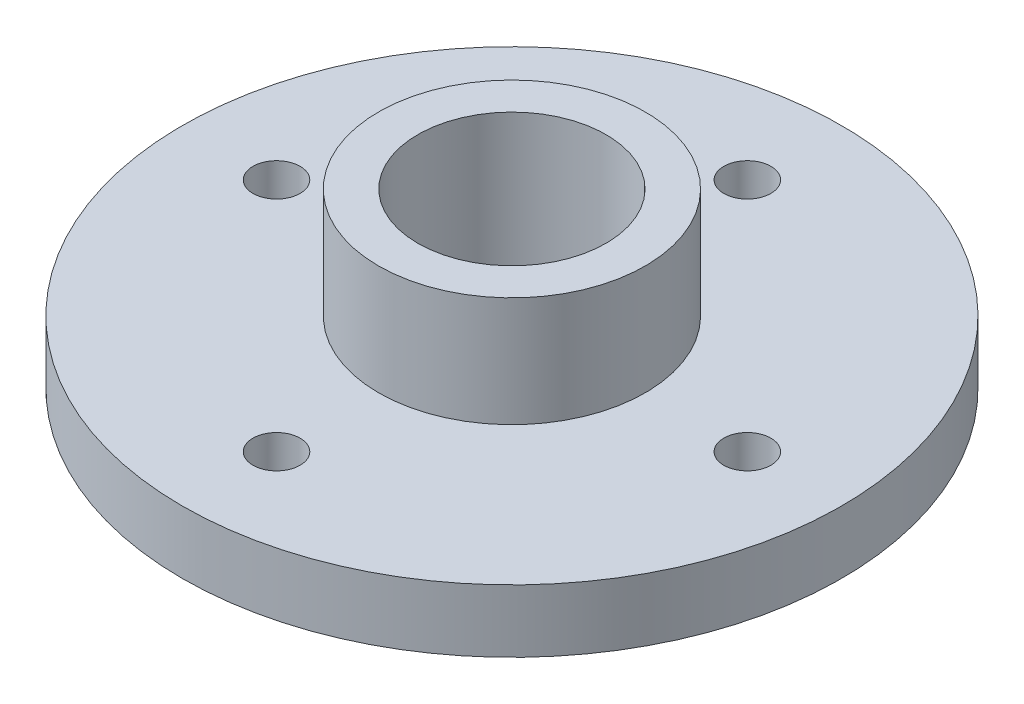
SolidWorks part; units mm, degrees
ref_plane "Vorne" through (0, 0, 0) normal (0, 0, 1) x (1, 0, 0)
ref_plane "Oben" through (0, 0, 0) normal (0, 1, 0) x (1, 0, 0)
ref_plane "Rechts" through (0, 0, 0) normal (1, 0, 0) x (0, 0, -1)
sketch "Skizze1" plane through (0, 0, 0) normal (0, 1, 0) x (1, 0, 0)
  circle A0 centre (0, 0) radius 10.5
  dimension "D1" = 21
extrude "Aufsatz-Linear austragen1" add sketch "Skizze1" along normal blind 2
sketch "Skizze2" plane through (0, 2, 0) normal (0, 1, 0) x (1, 0, 0)
  circle A0 centre (0, 0) radius 4.25
  circle A1 centre (0, 0) radius 3
  dimension "D1" = 8.5
  dimension "D2" = 6
extrude "Aufsatz-Linear austragen2" add sketch "Skizze2" along normal blind 3.5
sketch "Skizze3" plane through (0, 2, 0) normal (0, 1, 0) x (1, 0, 0)
  circle A0 centre (0, 7.5) radius 0.75
  circle A1 centre (0, -7.5) radius 0.75
  circle A2 centre (7.5, 0) radius 0.75
  circle A3 centre (-7.5, 0) radius 0.75
  circle A4 centre (0, 0) radius 10.5 construction
  point P10 (-10.5, 0)
  point P11 (0, 10.5)
  point P12 (10.5, 0)
  point P13 (0, -10.5)
  dimension "D1" = 3
  dimension "D2" = 3
  dimension "D3" = 3
  dimension "D4" = 3
  dimension "D5" = 1.5
  dimension "D6" = 1.5
  dimension "D7" = 1.5
  dimension "D8" = 1.5
extrude "Schnitt-Linear austragen1" cut sketch "Skizze3" against normal blind 3.5
sketch "Skizze4" plane through (0, 2, 0) normal (0, 1, 0) x (1, 0, 0)
  circle A0 centre (0, 0) radius 3
extrude "Schnitt-Linear austragen2" cut sketch "Skizze4" against normal blind 3.5
